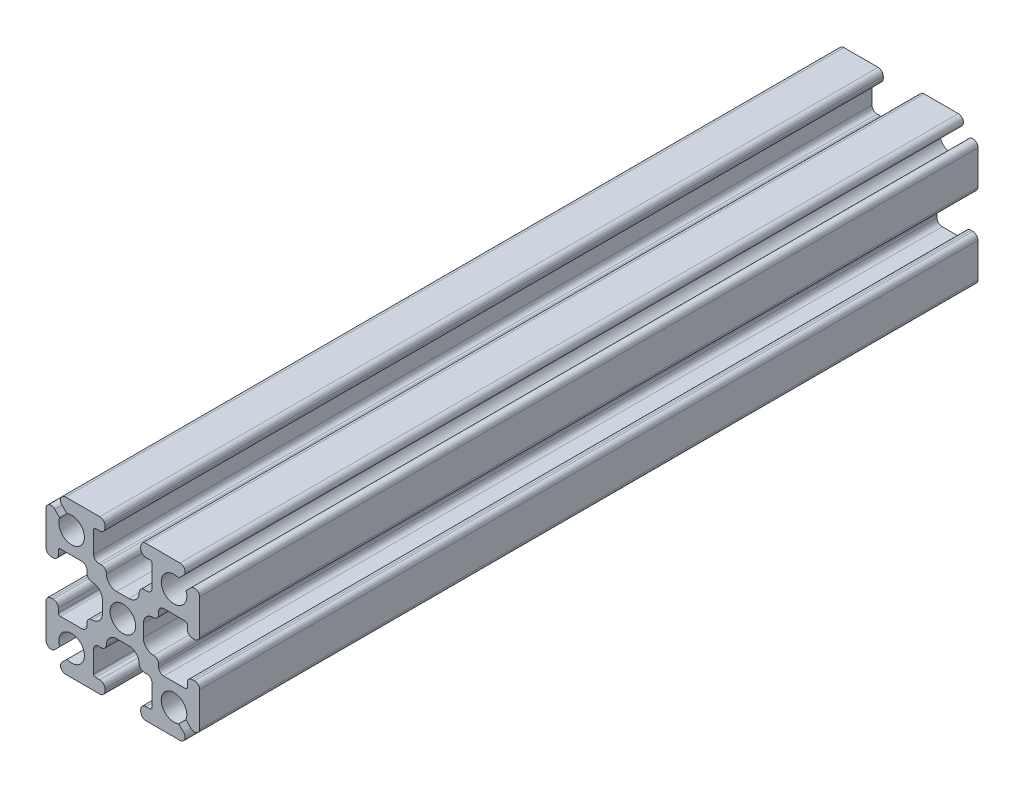
SolidWorks part; units mm, degrees
material "6063-T5"
ref_plane "Front Plane" through (0, 0, 0) normal (0, 0, 1) x (1, 0, 0)
ref_plane "Top Plane" through (0, 0, 0) normal (0, 1, 0) x (1, 0, 0)
ref_plane "Right Plane" through (0, 0, 0) normal (1, 0, 0) x (0, 0, -1)
sketch "Sketch1" plane through (0, 0, 0) normal (0, 0, 1) x (1, 0, 0)
  line L0 (6.6464, 5.9393) -> (6.1636, 5.4565)
  line L1 (5.4565, 6.1636) -> (5.9393, 6.6464)
  line L2 (5.5858, 7.5) -> (2.25, 7.5)
  line L3 (1.75, 7) -> (1.75, 6.8)
  line L4 (2.25, 6.3) -> (2.65, 6.3)
  line L5 (2.85, 6.1) -> (2.85, 4)
  line L6 (2.35, 3.5) -> (2.1, 3.5)
  line L7 (0.6, 2) -> (-0.6, 2)
  line L8 (-2.1, 3.5) -> (-2.35, 3.5)
  line L9 (-2.85, 4) -> (-2.85, 6.1)
  line L10 (-2.65, 6.3) -> (-2.25, 6.3)
  line L11 (-1.75, 6.8) -> (-1.75, 7)
  line L12 (-2.25, 7.5) -> (-5.5858, 7.5)
  line L13 (-5.9393, 6.6464) -> (-5.4565, 6.1636)
  line L14 (-6.1636, 5.4565) -> (-6.6464, 5.9393)
  line L15 (-7.5, 5.5858) -> (-7.5, 2.25)
  line L16 (-7, 1.75) -> (-6.8, 1.75)
  line L17 (-6.3, 2.25) -> (-6.3, 2.65)
  line L18 (-6.1, 2.85) -> (-4, 2.85)
  line L19 (-3.5, 2.35) -> (-3.5, 2.1)
  line L20 (-2, 0.6) -> (-2, -0.6)
  line L21 (-3.5, -2.1) -> (-3.5, -2.35)
  line L22 (-4, -2.85) -> (-6.1, -2.85)
  line L23 (-6.3, -2.65) -> (-6.3, -2.25)
  line L24 (-6.8, -1.75) -> (-7, -1.75)
  line L25 (-7.5, -2.25) -> (-7.5, -5.5858)
  line L26 (-6.6464, -5.9393) -> (-6.1636, -5.4565)
  line L27 (-5.4565, -6.1636) -> (-5.9393, -6.6464)
  line L28 (-5.5858, -7.5) -> (-2.25, -7.5)
  line L29 (-1.75, -7) -> (-1.75, -6.8)
  line L30 (-2.25, -6.3) -> (-2.65, -6.3)
  line L31 (-2.85, -6.1) -> (-2.85, -4)
  line L32 (-2.35, -3.5) -> (-2.1, -3.5)
  line L33 (-0.6, -2) -> (0.6, -2)
  line L34 (2.1, -3.5) -> (2.35, -3.5)
  line L35 (2.85, -4) -> (2.85, -6.1)
  line L36 (2.65, -6.3) -> (2.25, -6.3)
  line L37 (1.75, -6.8) -> (1.75, -7)
  line L38 (2.25, -7.5) -> (5.5858, -7.5)
  line L39 (5.9393, -6.6464) -> (5.4565, -6.1636)
  line L40 (6.1636, -5.4565) -> (6.6464, -5.9393)
  line L41 (7.5, -5.5858) -> (7.5, -2.25)
  line L42 (7, -1.75) -> (6.8, -1.75)
  line L43 (6.3, -2.25) -> (6.3, -2.65)
  line L44 (6.1, -2.85) -> (4, -2.85)
  line L45 (3.5, -2.35) -> (3.5, -2.1)
  line L46 (2, -0.6) -> (2, 0.6)
  line L47 (3.5, 2.1) -> (3.5, 2.35)
  line L48 (4, 2.85) -> (6.1, 2.85)
  line L49 (6.3, 2.65) -> (6.3, 2.25)
  line L50 (6.8, 1.75) -> (7, 1.75)
  line L51 (7.5, 2.25) -> (7.5, 5.5858)
  circle A0 centre (0, 0) radius 1.25
  arc A1 (6.1636, 5.4565) -> (5.4565, 6.1636) centre (5, 5) cw
  arc A2 (5.9393, 6.6464) -> (5.5858, 7.5) centre (5.5858, 7) ccw
  arc A3 (2.25, 7.5) -> (1.75, 7) centre (2.25, 7) ccw
  arc A4 (1.75, 6.8) -> (2.25, 6.3) centre (2.25, 6.8) ccw
  arc A5 (2.65, 6.3) -> (2.85, 6.1) centre (2.65, 6.1) cw
  arc A6 (2.85, 4) -> (2.35, 3.5) centre (2.35, 4) cw
  arc A7 (2.1, 3.5) -> (1.6, 3) centre (2.1, 3) ccw
  arc A8 (1.6, 3) -> (0.6, 2) centre (0.6, 3) cw
  arc A9 (-0.6, 2) -> (-1.6, 3) centre (-0.6, 3) cw
  arc A10 (-1.6, 3) -> (-2.1, 3.5) centre (-2.1, 3) ccw
  arc A11 (-2.35, 3.5) -> (-2.85, 4) centre (-2.35, 4) cw
  arc A12 (-2.85, 6.1) -> (-2.65, 6.3) centre (-2.65, 6.1) cw
  arc A13 (-2.25, 6.3) -> (-1.75, 6.8) centre (-2.25, 6.8) ccw
  arc A14 (-1.75, 7) -> (-2.25, 7.5) centre (-2.25, 7) ccw
  arc A15 (-5.5858, 7.5) -> (-5.9393, 6.6464) centre (-5.5858, 7) ccw
  arc A16 (-5.4565, 6.1636) -> (-6.1636, 5.4565) centre (-5, 5) cw
  arc A17 (-6.6464, 5.9393) -> (-7.5, 5.5858) centre (-7, 5.5858) ccw
  arc A18 (-7.5, 2.25) -> (-7, 1.75) centre (-7, 2.25) ccw
  arc A19 (-6.8, 1.75) -> (-6.3, 2.25) centre (-6.8, 2.25) ccw
  arc A20 (-6.3, 2.65) -> (-6.1, 2.85) centre (-6.1, 2.65) cw
  arc A21 (-4, 2.85) -> (-3.5, 2.35) centre (-4, 2.35) cw
  arc A22 (-3.5, 2.1) -> (-3, 1.6) centre (-3, 2.1) ccw
  arc A23 (-3, 1.6) -> (-2, 0.6) centre (-3, 0.6) cw
  arc A24 (-2, -0.6) -> (-3, -1.6) centre (-3, -0.6) cw
  arc A25 (-3, -1.6) -> (-3.5, -2.1) centre (-3, -2.1) ccw
  arc A26 (-3.5, -2.35) -> (-4, -2.85) centre (-4, -2.35) cw
  arc A27 (-6.1, -2.85) -> (-6.3, -2.65) centre (-6.1, -2.65) cw
  arc A28 (-6.3, -2.25) -> (-6.8, -1.75) centre (-6.8, -2.25) ccw
  arc A29 (-7, -1.75) -> (-7.5, -2.25) centre (-7, -2.25) ccw
  arc A30 (-7.5, -5.5858) -> (-6.6464, -5.9393) centre (-7, -5.5858) ccw
  arc A31 (-6.1636, -5.4565) -> (-5.4565, -6.1636) centre (-5, -5) cw
  arc A32 (-5.9393, -6.6464) -> (-5.5858, -7.5) centre (-5.5858, -7) ccw
  arc A33 (-2.25, -7.5) -> (-1.75, -7) centre (-2.25, -7) ccw
  arc A34 (-1.75, -6.8) -> (-2.25, -6.3) centre (-2.25, -6.8) ccw
  arc A35 (-2.65, -6.3) -> (-2.85, -6.1) centre (-2.65, -6.1) cw
  arc A36 (-2.85, -4) -> (-2.35, -3.5) centre (-2.35, -4) cw
  arc A37 (-2.1, -3.5) -> (-1.6, -3) centre (-2.1, -3) ccw
  arc A38 (-1.6, -3) -> (-0.6, -2) centre (-0.6, -3) cw
  arc A39 (0.6, -2) -> (1.6, -3) centre (0.6, -3) cw
  arc A40 (1.6, -3) -> (2.1, -3.5) centre (2.1, -3) ccw
  arc A41 (2.35, -3.5) -> (2.85, -4) centre (2.35, -4) cw
  arc A42 (2.85, -6.1) -> (2.65, -6.3) centre (2.65, -6.1) cw
  arc A43 (2.25, -6.3) -> (1.75, -6.8) centre (2.25, -6.8) ccw
  arc A44 (1.75, -7) -> (2.25, -7.5) centre (2.25, -7) ccw
  arc A45 (5.5858, -7.5) -> (5.9393, -6.6464) centre (5.5858, -7) ccw
  arc A46 (5.4565, -6.1636) -> (6.1636, -5.4565) centre (5, -5) cw
  arc A47 (6.6464, -5.9393) -> (7.5, -5.5858) centre (7, -5.5858) ccw
  arc A48 (7.5, -2.25) -> (7, -1.75) centre (7, -2.25) ccw
  arc A49 (6.8, -1.75) -> (6.3, -2.25) centre (6.8, -2.25) ccw
  arc A50 (6.3, -2.65) -> (6.1, -2.85) centre (6.1, -2.65) cw
  arc A51 (4, -2.85) -> (3.5, -2.35) centre (4, -2.35) cw
  arc A52 (3.5, -2.1) -> (3, -1.6) centre (3, -2.1) ccw
  arc A53 (3, -1.6) -> (2, -0.6) centre (3, -0.6) cw
  arc A54 (2, 0.6) -> (3, 1.6) centre (3, 0.6) cw
  arc A55 (3, 1.6) -> (3.5, 2.1) centre (3, 2.1) ccw
  arc A56 (3.5, 2.35) -> (4, 2.85) centre (4, 2.35) cw
  arc A57 (6.1, 2.85) -> (6.3, 2.65) centre (6.1, 2.65) cw
  arc A58 (6.3, 2.25) -> (6.8, 1.75) centre (6.8, 2.25) ccw
  arc A59 (7, 1.75) -> (7.5, 2.25) centre (7, 2.25) ccw
  arc A60 (7.5, 5.5858) -> (6.6464, 5.9393) centre (7, 5.5858) ccw
extrude "Boss-Extrude1" add sketch "Sketch1" along normal blind 76
